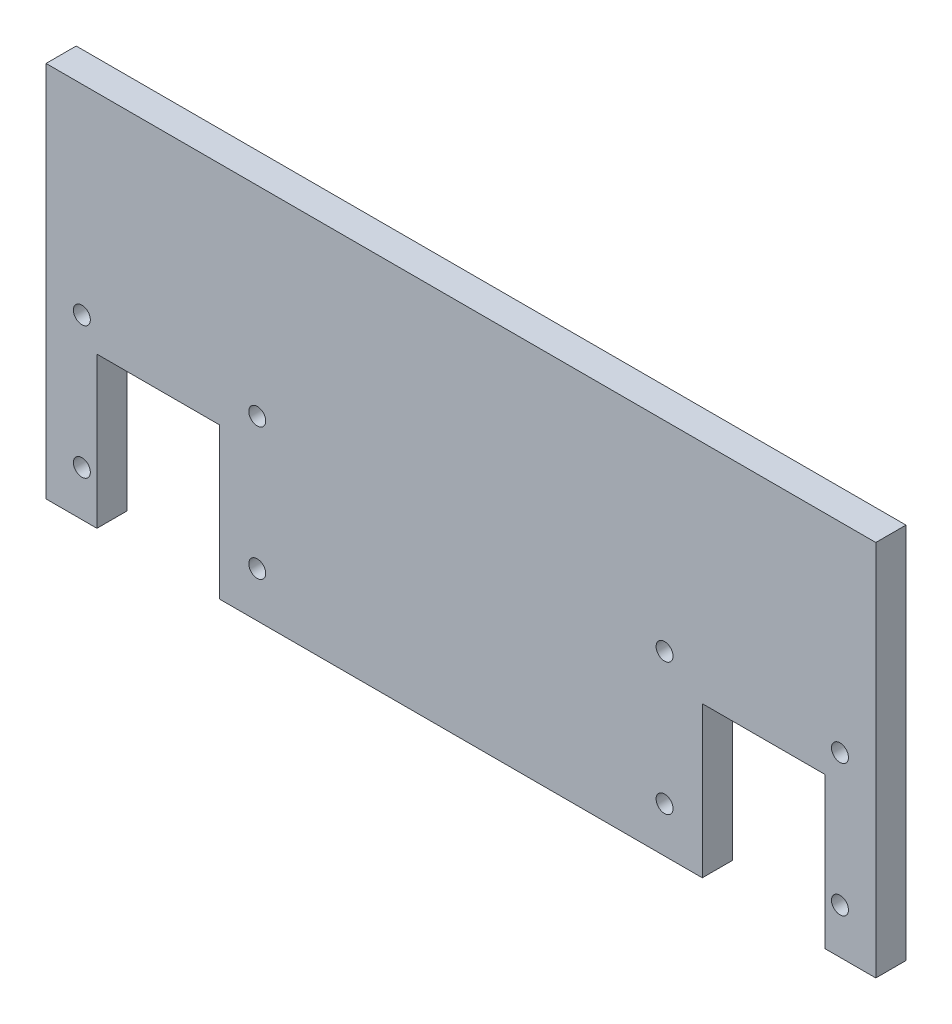
SolidWorks part; units mm, degrees
ref_plane "Front" through (0, 0, 0) normal (0, 0, 1) x (1, 0, 0)
ref_plane "Top" through (0, 0, 0) normal (0, 1, 0) x (1, 0, 0)
ref_plane "Right" through (0, 0, 0) normal (1, 0, 0) x (0, 0, -1)
sketch "Esquisse1" plane through (0, 0, 0) normal (0, 0, 1) x (1, 0, 0)
  line L1 (0, 0) -> (220, 0)
  line L2 (0, 0) -> (0, 100)
  line L3 (0, 100) -> (220, 100)
  line L4 (220, 0) -> (220, 100)
  dimension "D1" = 220
  dimension "D2" = 100
extrude "Boss.-Extru.1" add sketch "Esquisse1" along normal blind 8
sketch "Esquisse2" plane through (0, 0, 0) normal (0, -1, 0) x (1, 0, 0)
  line L0 (0, 4) -> (220, 4) construction
  line L1 (0, 8) -> (0, 0) construction
  line L2 (220, 8) -> (220, 0) construction
  line L3 (110, 4) -> (110, 28.0559) construction
  circle A0 centre (110, 4) radius 2
  circle A1 centre (213, 4) radius 2
  circle A2 centre (7, 4) radius 2
  dimension "D1" = 4
  dimension "D2" = 103
extrude "Enlèv. mat.-Extru.1" cut sketch "Esquisse2" against normal blind 8
sketch "Esquisse8" plane through (0, 0, 8) normal (0, 0, 1) x (1, 0, 0)
  line L0 (110, 0) -> (110, 100) construction
  line L1 (0, 0) -> (220, 0) construction
  line L2 (220, 100) -> (0, 100) construction
  line L3 (174, 0) -> (174, 40)
  line L4 (13.5, 0) -> (46, 0)
  line L5 (13.5, 0) -> (13.5, 40)
  line L6 (13.5, 40) -> (46, 40)
  line L7 (46, 0) -> (46, 40)
  line L8 (206.5, 40) -> (174, 40)
  line L9 (206.5, 0) -> (206.5, 40)
  line L10 (206.5, 0) -> (174, 0)
  dimension "D1" = 128
  dimension "D2" = 32.5
  dimension "D3" = 40
extrude "Enlèv. mat.-Extru.6" cut sketch "Esquisse8" against normal through all both and the other way through all
sketch "Esquisse10" plane through (0, 0, 8) normal (0, 0, 1) x (1, 0, 0)
  line L0 (9.5, 0) -> (9.5, 52.9697) construction
  line L1 (0, 0) -> (13.5, 0) construction
  line L2 (0, 100) -> (0, 0) construction
  line L3 (110, 0) -> (110, 48.9194) construction
  line L4 (46, 0) -> (174, 0) construction
  line L5 (32.75, 0) -> (32.75, 52.9697) construction
  circle A0 centre (9.5, 12) radius 2.25
  circle A1 centre (9.5, 47) radius 2.25
  circle A2 centre (210.5, 47) radius 2.25
  circle A3 centre (210.5, 12) radius 2.25
  circle A4 centre (56, 47) radius 2.25
  circle A5 centre (56, 12) radius 2.25
  circle A6 centre (164, 12) radius 2.25
  circle A7 centre (164, 47) radius 2.25
  dimension "D2" = 4.5
  dimension "D3" = 35
  dimension "D4" = 12
  dimension "D5" = 46.5
  dimension "D1" = 9.5
extrude "Enlèv. mat.-Extru.8" cut sketch "Esquisse10" against normal through all both and the other way through all
